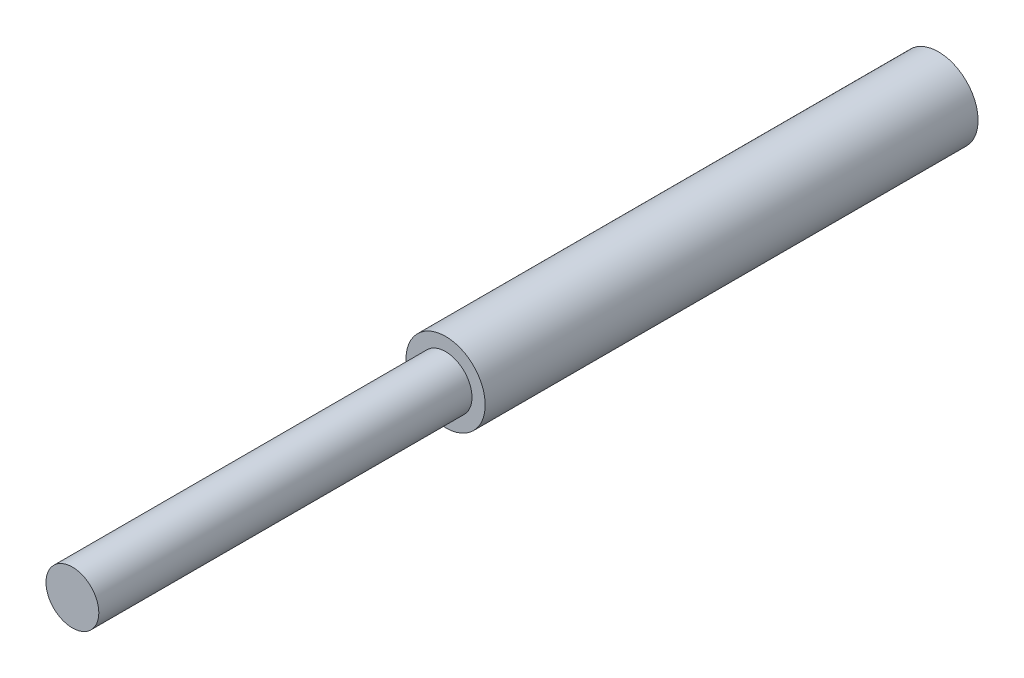
SolidWorks part; units mm, degrees
material "Aluminum"
ref_plane "Front Plane" through (0, 0, 0) normal (0, 0, 1) x (1, 0, 0)
ref_plane "Top Plane" through (0, 0, 0) normal (0, 1, 0) x (1, 0, 0)
ref_plane "Right Plane" through (0, 0, 0) normal (1, 0, 0) x (0, 0, -1)
sketch "Sketch1" plane through (0, 0, 0) normal (0, 0, 1) x (1, 0, 0)
  circle A0 centre (0, 0) radius 1.5
  dimension "D1" = 3
extrude "Boss-Extrude1" add sketch "Sketch1" along normal blind 21.2
sketch "Sketch2" plane through (0, 0, 0) normal (0, 0, -1) x (-1, 0, 0)
  circle A0 centre (0, 0) radius 2.25
  dimension "D1" = 4.5
extrude "Boss-Extrude2" add sketch "Sketch2" along normal blind 28
sketch "Sketch3" plane through (0, 0, -28) normal (0, 0, -1) x (-1, 0, 0)
  circle A0 centre (0, 0) radius 1.5
  dimension "D1" = 3
extrude "Cut-Extrude1" cut sketch "Sketch3" against normal blind 6
